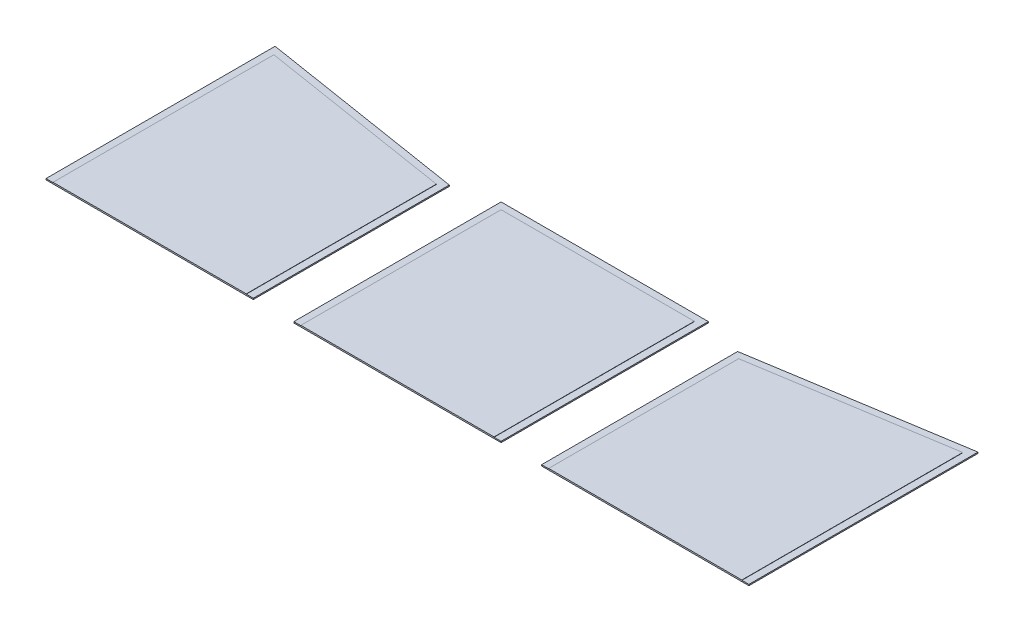
SolidWorks part; units mm, degrees
ref_plane "Front Plane" through (0, 0, 0) normal (0, 0, 1) x (1, 0, 0)
ref_plane "Top Plane" through (0, 0, 0) normal (0, 1, 0) x (1, 0, 0)
ref_plane "Right Plane" through (0, 0, 0) normal (1, 0, 0) x (0, 0, -1)
sketch "Sketch1" plane through (0, 0, 0) normal (0, 1, 0) x (1, 0, 0)
  line L0 (-76.75, 76.75) -> (-76.75, -76.75)
  line L1 (-76.75, -76.75) -> (76.75, -76.75)
  line L2 (76.75, -76.75) -> (76.75, 76.75)
  line L3 (76.75, 76.75) -> (-76.75, 76.75)
  line L4 (-76.75, -76.75) -> (76.75, 76.75) construction
  line L5 (-76.75, 76.75) -> (76.75, -76.75) construction
  line L6 (-260.2562, 92.8952) -> (-260.25, -76.75)
  line L7 (-260.25, -76.75) -> (-106.75, -76.75)
  line L8 (-106.75, -76.75) -> (-106.75, 68.3995)
  line L9 (-106.75, 68.3995) -> (-260.2562, 92.8952)
  line L10 (-343.936, -76.75) -> (357.0432, -76.75) construction
  line L11 (260.2562, 92.8952) -> (106.75, 68.3995)
  line L12 (106.75, 68.3995) -> (106.75, -76.75)
  line L13 (106.75, -76.75) -> (260.25, -76.75)
  line L14 (260.25, -76.75) -> (260.2562, 92.8952)
  point P4 (0, 0)
  dimension "D1" = 153.5
  dimension "D2" = 153.5
  dimension "D3" = 145.1495
  dimension "D4" = 155.4484
  dimension "D5" = 99.067
  dimension "D6" = 30
  dimension "D7" = 153.5
  dimension "D8" = 145.1495
  dimension "D9" = 155.4484
  dimension "D10" = 99.067
  dimension "D11" = 30
extrude "Boss-Extrude1" add sketch "Sketch1" along normal blind 0.9
sketch "Sketch2" plane through (0, 0.9, 0) normal (0, 1, 0) x (1, 0, 0)
  line L0 (-76.75, 76.75) -> (-76.75, -76.75) construction
  line L1 (-76.75, -76.75) -> (76.75, -76.75) construction
  line L2 (-71.55, -76.75) -> (-71.55, 71.55)
  line L3 (-71.55, 71.55) -> (71.55, 71.55)
  line L4 (71.55, 71.55) -> (71.55, -76.75)
  line L5 (71.55, -76.75) -> (-71.55, -76.75)
  line L6 (-111.95, -76.75) -> (-111.95, 63.9635)
  line L7 (-260.25, -76.75) -> (-106.75, -76.75) construction
  line L8 (-111.95, 63.9635) -> (-255.056, 86.7996)
  line L9 (-255.056, 86.7996) -> (-255.05, -76.75)
  line L10 (-255.05, -76.75) -> (-111.95, -76.75)
  line L11 (111.95, -76.75) -> (111.95, 63.9635)
  line L12 (106.75, -76.75) -> (260.25, -76.75) construction
  line L13 (111.95, 63.9635) -> (255.056, 86.7996)
  line L14 (255.056, 86.7996) -> (255.05, -76.75)
  line L15 (255.05, -76.75) -> (111.95, -76.75)
  line L16 (-106.75, 68.3995) -> (-260.2562, 92.8952) construction
  line L17 (260.2562, 92.8952) -> (106.75, 68.3995) construction
  line L18 (76.75, -76.75) -> (76.75, 76.75) construction
  line L19 (76.75, 76.75) -> (-76.75, 76.75) construction
  line L20 (-260.2562, 92.8952) -> (-260.25, -76.75) construction
  line L21 (106.75, 68.3995) -> (106.75, -76.75) construction
  line L22 (260.25, -76.75) -> (260.2562, 92.8952) construction
  point P2 (0, 0)
  point P31 (-428.3794, 28.4884)
  dimension "D1" = 5.2
  dimension "D2" = 5.2
  dimension "D3" = 5.2
  dimension "D4" = 5.2
  dimension "D5" = 5.2
  dimension "D6" = 5.2
  dimension "D7" = 5.2
  dimension "D8" = 5.2
  dimension "D9" = 5.2
extrude "Boss-Extrude2" add sketch "Sketch2" along normal blind 0.2
sketch "Sketch3" plane through (0, 1.1, 0) normal (0, 1, 0) x (1, 0, 0)
  line L0 (-260.25, -76.75) -> (-224.55, -76.75) construction
  line L1 (-255.05, -76.75) -> (-111.95, -76.75) construction
  line L2 (-224.55, -76.75) -> (-224.55, 87.1974) construction
  line L3 (-106.75, 68.3995) -> (-260.2562, 92.8952) construction
  line L4 (260.25, -76.75) -> (224.55, -76.75) construction
  line L5 (111.95, -76.75) -> (255.05, -76.75) construction
  line L6 (224.55, -76.75) -> (224.55, 87.1974) construction
  line L7 (260.2562, 92.8952) -> (106.75, 68.3995) construction
  dimension "D1" = 35.7
  dimension "D2" = 35.7
